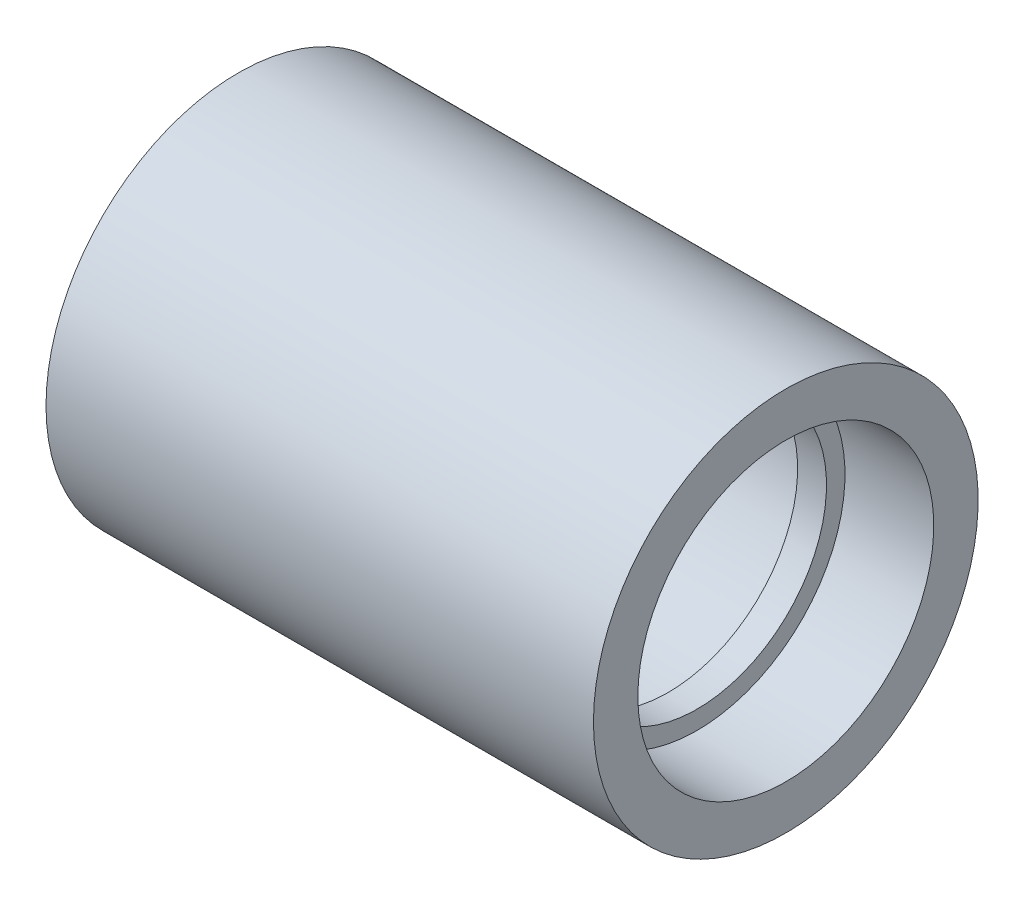
SolidWorks part; units mm, degrees
ref_plane "Front Plane" through (0, 0, 0) normal (0, 0, 1) x (1, 0, 0)
ref_plane "Top Plane" through (0, 0, 0) normal (0, 1, 0) x (1, 0, 0)
ref_plane "Right Plane" through (0, 0, 0) normal (1, 0, 0) x (0, 0, -1)
sketch "Sketch1" plane through (0, 0, 0) normal (0, 0, 1) x (1, 0, 0)
  line L0 (0, 0) -> (112.825, 0) construction
  line L10 (12.3374, 22) -> (12.3374, 23.5)
  line L11 (12.3374, 23.5) -> (-1.6626, 23.5)
  line L12 (-1.6626, 23.5) -> (-1.6626, 26)
  line L13 (-1.6626, 26) -> (72.3374, 26)
  line L14 (72.3374, 26) -> (72.3374, 20)
  line L15 (72.3374, 20) -> (60.3374, 20)
  line L16 (60.3374, 20) -> (60.3374, 17.5)
  line L17 (60.3374, 17.5) -> (56.4374, 17.5)
  line L18 (56.4374, 17.5) -> (56.4374, 22)
  line L19 (56.4374, 22) -> (12.3374, 22)
  point P8 (65.4192, 22)
  point P11 (58.3874, 17.5)
  dimension "D1" = 74
  dimension "D2" = 23.5
  dimension "D3" = 44.1
  dimension "D4" = 14
  dimension "D5" = 12
  dimension "D6" = 22
  dimension "D7" = 20
  dimension "D8" = 17.5
  dimension "D9" = 26
revolve "Revolve1" add sketch "Sketch1" angle 360 about L0
